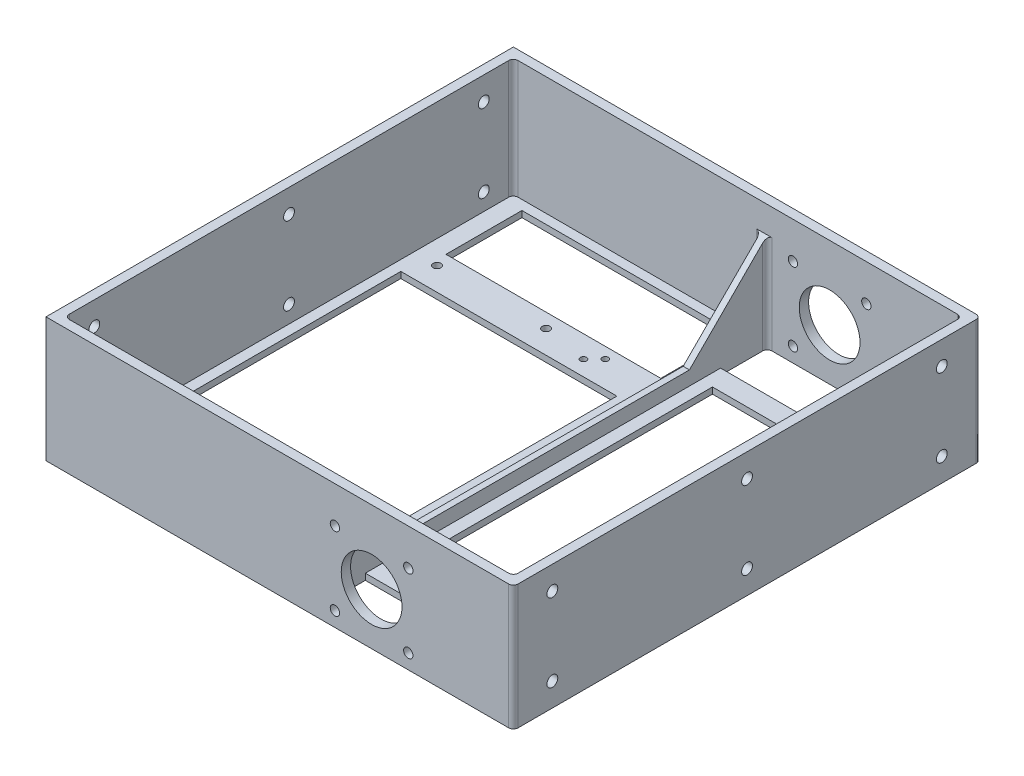
SolidWorks part; units mm, degrees
ref_plane "Спереди" through (0, 0, 0) normal (0, 0, 1) x (1, 0, 0)
ref_plane "Сверху" through (0, 0, 0) normal (0, 1, 0) x (1, 0, 0)
ref_plane "Справа" through (0, 0, 0) normal (1, 0, 0) x (0, 0, -1)
sketch "Эскиз1" plane through (0, 0, 0) normal (0, 1, 0) x (1, 0, 0)
  line L1 (-150, -150) -> (150, -150)
  line L2 (-150, -150) -> (-150, 150)
  line L3 (-150, 150) -> (150, 150)
  line L4 (150, -150) -> (150, 150)
  line L5 (0, 150) -> (0, -150) construction
  line L6 (-150, 0) -> (150, 0) construction
  point P0 (0, 0)
  dimension "D1" = 300
  dimension "D2" = 300
extrude "Бобышка-Вытянуть1" add sketch "Эскиз1" along normal blind 4
sketch "Эскиз2" plane through (0, 4, 0) normal (0, 1, 0) x (1, 0, 0)
  line L0 (0, 157.2547) -> (0, 0) construction
  line L1 (150, 150) -> (-144, 150)
  line L2 (150, 150) -> (150, 0.2395)
  line L4 (-144, 150) -> (-144, 144)
  line L5 (0, 0) -> (241.6766, 0) construction
  line L6 (-144, -150) -> (-144, -144)
  line L8 (150, -150) -> (150, 0.2395)
  line L9 (150, -150) -> (-144, -150)
  line L10 (-144, 144) -> (144, 144)
  line L11 (144, 144) -> (144, -144)
  line L12 (-144, -144) -> (144, -144)
  point P14 (144, 0)
  dimension "D1" = 6
  dimension "D2" = 6
  dimension "D3" = 294
extrude "Бобышка-Вытянуть2" add sketch "Эскиз2" along normal blind 76
fillet "Скругление1" radius 3 2 edges at (150, 40, -150) (150, 40, 150)
sketch "Эскиз3" plane through (0, 0, 150) normal (0, 0, 1) x (1, 0, 0)
  line L0 (59, 89.0482) -> (59, 33) construction
  line L1 (59, 33) -> (167.6042, 33) construction
  line L6 (35.45, 9.45) -> (82.55, 9.45) construction
  line L7 (35.45, 9.45) -> (35.45, 56.55) construction
  line L8 (35.45, 56.55) -> (82.55, 56.55) construction
  line L9 (82.55, 9.45) -> (82.55, 56.55) construction
  line L10 (59, 56.55) -> (59, 9.45) construction
  line L11 (35.45, 33) -> (82.55, 33) construction
  line L14 (150, 80) -> (150, 0) construction
  line L15 (147, 0) -> (147, 80) construction
  line L16 (-150, 0) -> (147, 0) construction
  circle A0 centre (35.45, 56.55) radius 3
  circle A1 centre (82.55, 56.55) radius 3
  circle A2 centre (35.45, 9.45) radius 3
  circle A3 centre (82.55, 9.45) radius 3
  circle A4 centre (59, 33) radius 19.5
  point P13 (144.3287, 87.1893)
  point P17 (147, 77.8894)
  point P21 (193.8855, 43.9417)
  point P22 (152.7634, 76.8199)
  point P25 (133.6224, 76.927)
  dimension "D4" = 6
  dimension "D5" = 39
  dimension "D1" = 29
  dimension "D2" = 91
  dimension "D3" = 47.1
extrude "Вырез-Вытянуть1" cut sketch "Эскиз3" against normal through all both and the other way through all
sketch "Эскиз4" plane through (0, 4, 0) normal (0, 1, 0) x (1, 0, 0)
  line L0 (-150, -150) -> (-144, -150) construction
  line L1 (-150, 150) -> (-144, 150)
  line L2 (-150, 150) -> (-150, -150)
  line L3 (-150, -150) -> (-144, -150)
  line L4 (-144, 150) -> (-144, -150)
  dimension "D1" = 6
extrude "Бобышка-Вытянуть3" add sketch "Эскиз4" along normal up to surface (76 mm away) up to face at (30.7243, 80, 0)
sketch "Эскиз7" plane through (0, 4, 0) normal (0, 1, 0) x (1, 0, 0)
  line L0 (0, 158.6534) -> (0, 0) construction
  line L1 (0, 0) -> (246.672, 0) construction
  line L8 (47, 0) -> (147, 0) construction
  line L10 (144, 144) -> (144, -144) construction
  line L11 (-30, -75) -> (134, -75) construction
  line L12 (-30, -75) -> (-30, 75) construction
  line L13 (-30, 75) -> (134, 75) construction
  line L14 (134, -75) -> (134, 75) construction
  line L15 (52, 75) -> (52, -75) construction
  line L16 (-30, 0) -> (134, 0) construction
  line L18 (-23, -82) -> (127, -82) construction
  line L19 (-23, -82) -> (-23, 82) construction
  line L20 (-23, 82) -> (127, 82) construction
  line L21 (127, -82) -> (127, 82) construction
  line L22 (52, 82) -> (52, -82) construction
  line L23 (-23, 0) -> (127, 0) construction
  circle A16 centre (127, 82) radius 2
  circle A17 centre (134, 75) radius 2
  circle A18 centre (-23, 82) radius 2
  circle A19 centre (-30, 75) radius 2
  circle A20 centre (127, -82) radius 2
  circle A22 centre (134, -75) radius 2
  circle A23 centre (-30, -75) radius 2
  circle A24 centre (-23, -82) radius 2
  point P5 (0, 0)
  point P44 (52, 0)
  point P50 (52, 0)
  dimension "D12" = 4
  dimension "D7" = 164
  dimension "D8" = 150
  dimension "D9" = 10
  dimension "D10" = 164
  dimension "D11" = 150
extrude "Вырез-Вытянуть3" cut sketch "Эскиз7" against normal blind 10
sketch "Эскиз14" plane through (0, 4, 0) normal (0, 1, 0) x (1, 0, 0)
  line L0 (59, 159.053) -> (59, -165.8467) construction
  line L1 (150, -147) -> (150, 147) construction
  line L2 (-144, 144) -> (144, 144) construction
  line L3 (19, 114) -> (99, 114)
  line L4 (19, 114) -> (19, 144)
  line L5 (19, 144) -> (99, 144)
  line L6 (99, 114) -> (99, 144)
  line L7 (59, 144) -> (59, 114) construction
  line L8 (19, 129) -> (99, 129) construction
  line L9 (0, 0) -> (180.733, 0) construction
  line L10 (19, -144) -> (99, -144)
  line L11 (99, -114) -> (99, -144)
  line L12 (19, -114) -> (99, -114)
  line L13 (19, -114) -> (19, -144)
  point P4 (59, 129)
  dimension "D1" = 91
  dimension "D2" = 80
  dimension "D3" = 30
extrude "Вырез-Вытянуть9" cut sketch "Эскиз14" against normal blind 20
sketch "Эскиз15" plane through (-150, 0, 0) normal (-1, 0, 0) x (0, 0, 1)
  line L0 (0, 107.7828) -> (0, 40) construction
  line L1 (0, 40) -> (185.6693, 40) construction
  line L2 (-150, 0) -> (150, 0) construction
  line L3 (-171.7731, 65) -> (170.5378, 65) construction
  circle A0 centre (0, 65) radius 3.5
  circle A1 centre (125, 65) radius 3.5
  circle A2 centre (-125, 65) radius 3.5
  circle A3 centre (-125, 15) radius 3.5
  circle A4 centre (125, 15) radius 3.5
  circle A5 centre (0, 15) radius 3.5
  point P12 (98.9947, 65)
  dimension "D3" = 7
  dimension "D4" = 125
  dimension "D1" = 40
  dimension "D2" = 25
extrude "Вырез-Вытянуть10" cut sketch "Эскиз15" against normal through all both and the other way through all
sketch "Эскиз16" plane through (0, 4, 0) normal (0, 1, 0) x (1, 0, 0)
  line L0 (19, -144) -> (-144, -144) construction
  line L1 (19, 144) -> (15, 144)
  line L2 (19, 144) -> (19, -144)
  line L3 (19, -144) -> (15, -144)
  line L4 (15, 144) -> (15, -144)
  dimension "D1" = 4
extrude "Бобышка-Вытянуть5" add sketch "Эскиз16" along normal blind 9
chamfer "Фаска3" distance 50 angle 45 2 edges at (17, 13, 144) (17, 13, -144)
sketch "Эскиз17" plane through (0, 4, 0) normal (0, 1, 0) x (1, 0, 0)
  line L0 (0, 160.2519) -> (0, 0) construction
  line L1 (0, 0) -> (-191.9226, 0) construction
  line L2 (-144, 144) -> (144, 144) construction
  line L3 (-64, 154.062) -> (-64, -240.8411) construction
  line L4 (-144, -144) -> (-144, 144) construction
  circle A0 centre (0, 134) radius 2.25
  circle A1 centre (0, 104) radius 2.25
  circle A2 centre (-64, 134) radius 2.25
  circle A3 centre (-64, 104) radius 2.25
  circle A4 centre (-128, 134) radius 2.25
  circle A5 centre (-128, 104) radius 2.25
  circle A6 centre (-128, -104) radius 2.25
  circle A7 centre (-128, -134) radius 2.25
  circle A8 centre (-64, -104) radius 2.25
  circle A9 centre (-64, -134) radius 2.25
  circle A10 centre (0, -104) radius 2.25
  circle A11 centre (0, -134) radius 2.25
  circle A12 centre (-129, 0) radius 2.5
  circle A13 centre (-59, 0) radius 2.5
  circle A14 centre (-59, 40) radius 2.5
  circle A15 centre (-129, 40) radius 2.5
  circle A16 centre (-59, 80) radius 2.5
  circle A17 centre (-129, 80) radius 2.5
  circle A18 centre (-59, -40) radius 2.5
  circle A19 centre (-129, -40) radius 2.5
  circle A20 centre (-59, -80) radius 2.5
  circle A21 centre (-129, -80) radius 2.5
  dimension "D1" = 4.5
  dimension "D2" = 30
  dimension "D3" = 10
  dimension "D5" = 3
  dimension "D6" = 70
  dimension "D7" = 15
  dimension "D4" = 3
extrude "Вырез-Вытянуть11" cut sketch "Эскиз17" against normal blind 6
sketch "Эскиз18" plane through (0, 4, 0) normal (0, 1, 0) x (1, 0, 0)
  line L0 (-132.3777, -137.8726) -> (5.4949, -137.8726)
  line L1 (26.8752, -102.3054) -> (119.1898, -102.3054)
  line L2 (26.8752, -102.3054) -> (26.8752, 100.9067)
  line L3 (26.8752, 100.9067) -> (119.1898, 100.9067)
  line L4 (119.1898, -102.3054) -> (119.1898, 100.9067)
  line L7 (-137.373, -68.5367) -> (1.2988, -68.5367)
  line L8 (-137.373, -68.5367) -> (-137.373, 65.1398)
  line L9 (-137.373, 65.1398) -> (1.2988, 65.1398)
  line L10 (1.2988, -68.5367) -> (1.2988, 65.1398)
  line L13 (-132.3777, 89.1176) -> (5.4949, 89.1176)
  line L14 (-132.3777, 89.1176) -> (-132.3777, 137.8726)
  line L15 (-132.3777, 137.8726) -> (5.4949, 137.8726)
  line L16 (5.4949, 89.1176) -> (5.4949, 137.8726)
  line L19 (5.4949, -89.9169) -> (5.4949, -137.8726)
  line L20 (-132.3777, -89.9169) -> (5.4949, -89.9169)
  line L21 (-132.3777, -89.9169) -> (-132.3777, -137.8726)
  point P0 (0, 0)
  point P21 (120.7884, 0)
  point P22 (0, 0)
extrude "Вырез-Вытянуть12" cut sketch "Эскиз18" against normal blind 6
fillet "Скругление4" radius 3 8 edges at (19, 31.5, 144) (15, 33.5, 144) (144, 42, 144) (-144, 42, 144) (19, 31.5, -144) (15, 33.5, -144) (144, 42, -144) (-144, 42, -144)
